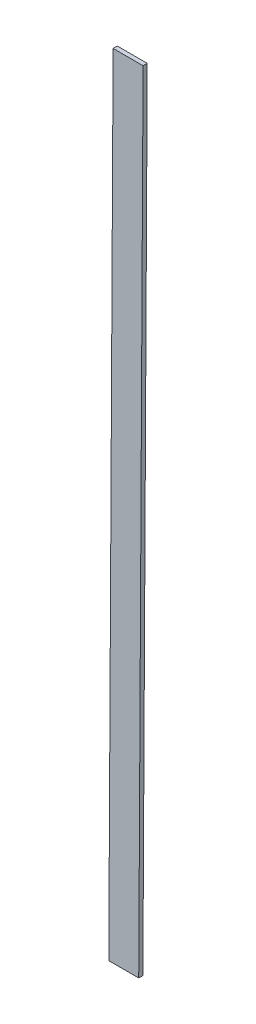
SolidWorks part; units mm, degrees
material "Balsa"
ref_plane "Front Plane" through (0, 0, 0) normal (0, 0, 1) x (1, 0, 0)
ref_plane "Top Plane" through (0, 0, 0) normal (0, 1, 0) x (1, 0, 0)
ref_plane "Right Plane" through (0, 0, 0) normal (1, 0, 0) x (0, 0, -1)
sketch "Sketch1" plane through (0, 0, 0) normal (0, 0, 1) x (1, 0, 0)
  line L0 (14.6292, -88.3608) -> (16.2944, 213.9064)
  line L1 (16.2944, 213.9064) -> (27.7283, 213.9064)
  line L2 (27.7283, 213.9064) -> (26.0631, -88.3608)
  line L3 (26.0631, -88.3608) -> (14.6292, -88.3608)
extrude "Boss-Extrude1" add sketch "Sketch1" along normal blind 1.5875 contours L0 L1 L2 L3
